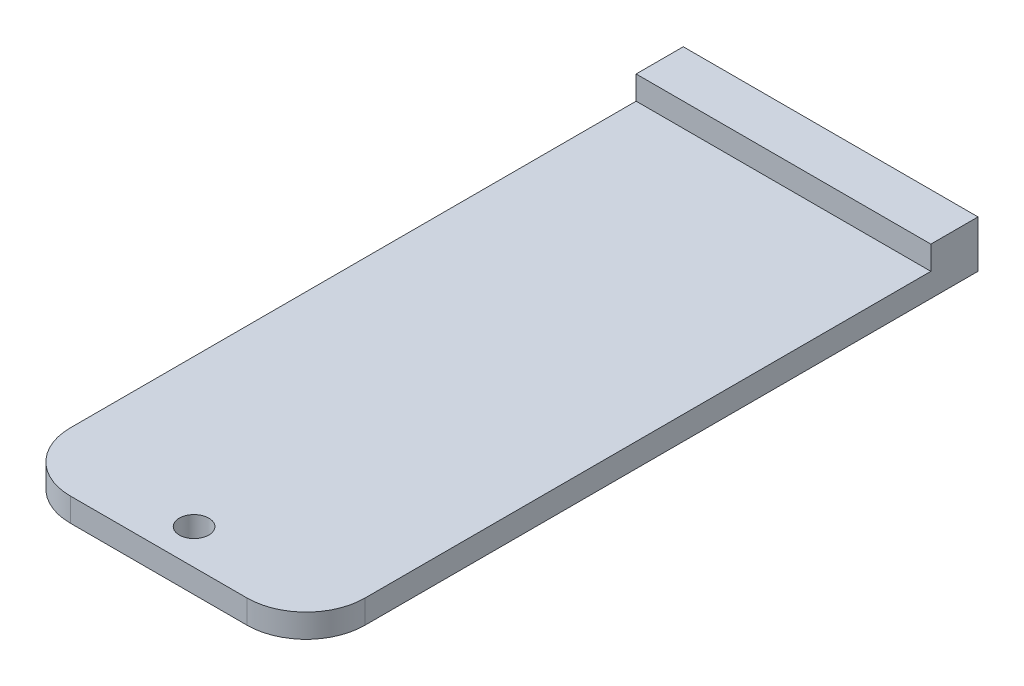
SolidWorks part; units mm, degrees
material "PVC rigido"
ref_plane "Piano frontale" through (0, 0, 0) normal (0, 0, 1) x (1, 0, 0)
ref_plane "Piano superiore" through (0, 0, 0) normal (0, 1, 0) x (1, 0, 0)
ref_plane "Piano destro" through (0, 0, 0) normal (1, 0, 0) x (0, 0, -1)
sketch "Schizzo1" plane through (0, 0, 0) normal (0, 0, 1) x (1, 0, 0)
  line L1 (-37.5, 8) -> (-12.5, 8)
  line L2 (-37.5, 8) -> (-37.5, 10)
  line L3 (-37.5, 10) -> (-12.5, 10)
  line L4 (-12.5, 8) -> (-12.5, 10)
extrude "Estrusione-Estrusione1" add sketch "Schizzo1" against normal up to surface (47 mm away)
ref_plane "Piano1" through (0, 0, -23.5) normal (0, 0, 1) x (1, 0, 0)
sketch "Schizzo2" plane through (0, 0, 0) normal (0, 0, 1) x (1, 0, 0)
  line L1 (-37.5, 10) -> (-12.5, 10)
  line L2 (-37.5, 10) -> (-37.5, 8)
  line L3 (-37.5, 8) -> (-12.5, 8)
  line L4 (-12.5, 10) -> (-12.5, 8)
extrude "Estrusione-Estrusione2" add sketch "Schizzo2" along normal blind 6
hole_wizard "Foro filettato M3x0.5-1" positions "Schizzo4" profile "Schizzo3" tap size "M3x0.5" standard "Ansi Metric" end condition through all
sketch "Schizzo4" plane through (0, 10, 0) normal (0, 1, 0) x (1, 0, 0)
  line L0 (-37.5, -3) -> (-25, -3) construction
  line L1 (-37.5, 47) -> (-37.5, -6) construction
  line L2 (-25, -3) -> (-12.5, -3) construction
  line L3 (-12.5, 47) -> (-12.5, -6) construction
  line L5 (-25, -3) -> (-25, -6) construction
  line L6 (-12.5, -6) -> (-37.5, -6) construction
  point P0 (-25, -3)
  dimension "D1" = 3
sketch "Schizzo3" plane through (-25, 10, 3) normal (1, 0, 0) x (0, 0, 1)
  line L0 (0, 0) -> (0, 2)
  line L1 (0, 2) -> (1.25, 2)
  line L2 (1.25, 2) -> (1.25, 0)
  line L5 (1.25, 0) -> (0, 0)
  line L11 (0, -6.35) -> (0, 107.95) construction
  dimension "Thru Tap Drill Dia." = 2.5
  dimension "Thru Tap Drill Depth" = 2
cosmetic thread "Filettatura del foro1" parameters "D2"=3
fillet "Raccordo1" radius 5 2 edges at (-37.5, 9, 6) (-12.5, 9, 6)
mirror "Specchia1" [suppressed] about plane through (0, 0, -23.5) normal (0, 0, 1)
sketch "Schizzo5" plane through (0, 0, -47) normal (0, 0, -1) x (-1, 0, 0)
  line L0 (12.5, 10) -> (12.5, 12)
  line L1 (12.5, 8) -> (37.5, 8)
  line L2 (12.5, 8) -> (12.5, 10)
  line L3 (12.5, 10) -> (37.5, 10) construction
  line L4 (37.5, 8) -> (37.5, 10)
  line L5 (12.5, 12) -> (37.5, 12)
  line L6 (37.5, 12) -> (37.5, 10)
extrude "Estrusione-Estrusione3" add sketch "Schizzo5" along normal blind 4
